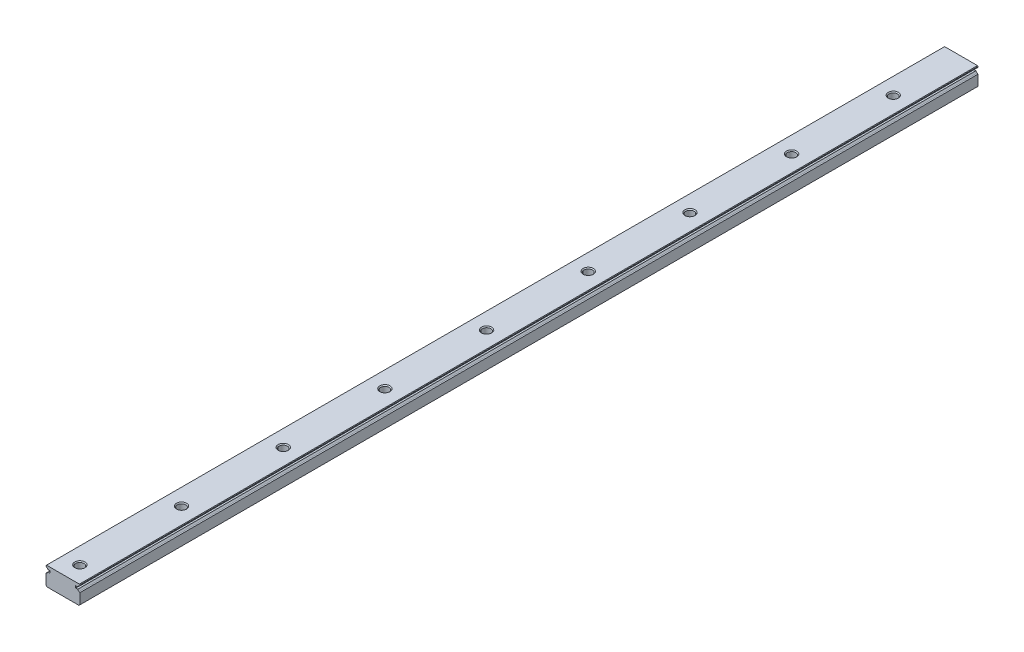
SolidWorks part; units mm, degrees
ref_plane "Plan de face" through (0, 0, 0) normal (0, 0, 1) x (1, 0, 0)
ref_plane "Plan de dessus" through (0, 0, 0) normal (0, 1, 0) x (1, 0, 0)
ref_plane "Plan de droite" through (0, 0, 0) normal (1, 0, 0) x (0, 0, -1)
ref_plane "Plan1" through (0, 0, 0) normal (0, -1, 0) x (1, 0, 0)
sketch "Esquisse1" plane through (0, 0, 0) normal (0, -1, 0) x (1, 0, 0)
  line L0 (-10, -280) -> (10, -280)
  line L1 (10, -280) -> (10, 250)
  line L2 (10, 250) -> (-10, 250)
  line L3 (-10, 250) -> (-10, -280)
  dimension "D1" = 530
  dimension "D2" = 20
extrude "Boss.-Extru.1" add sketch "Esquisse1" against normal blind 11
sketch "Esquisse2" plane through (0, 0, -280) normal (0, 0, -1) x (-1, 0, 0)
  line L0 (10, 7.9) -> (10, 10.2238)
  line L1 (10, 10.2238) -> (9.44, 9.9006)
  line L2 (8.7177, 9.1) -> (7.5, 9.1)
  line L3 (7.5, 9.1) -> (7.5, 7.9)
  line L4 (7.5, 7.9) -> (10, 7.9)
  arc A0 (9.44, 9.9006) -> (8.7177, 9.1) centre (10.315, 8.385) ccw
extrude "Enlèv. mat.-Extru.1" cut sketch "Esquisse2" against normal through all
sketch "Esquisse3" plane through (0, 0, -280) normal (0, 0, -1) x (-1, 0, 0)
  line L0 (9.44, 7.0994) -> (10, 6.7761)
  line L1 (10, 6.7761) -> (10, 7.9)
  line L2 (10, 7.9) -> (8.7177, 7.9)
  arc A0 (8.7177, 7.9) -> (9.44, 7.0994) centre (10.315, 8.615) ccw
extrude "Enlèv. mat.-Extru.2" cut sketch "Esquisse3" against normal through all
sketch "Esquisse4" plane through (0, 0, -280) normal (0, 0, -1) x (-1, 0, 0)
  line L0 (-10, 9.1) -> (-10, 6.7761)
  line L1 (-10, 6.7761) -> (-9.44, 7.0994)
  line L2 (-8.7177, 7.9) -> (-7.5, 7.9)
  line L3 (-7.5, 7.9) -> (-7.5, 9.1)
  line L4 (-7.5, 9.1) -> (-10, 9.1)
  arc A0 (-9.44, 7.0994) -> (-8.7177, 7.9) centre (-10.315, 8.615) ccw
extrude "Enlèv. mat.-Extru.3" cut sketch "Esquisse4" against normal through all
sketch "Esquisse5" plane through (0, 0, -280) normal (0, 0, -1) x (-1, 0, 0)
  line L0 (-9.44, 9.9006) -> (-10, 10.2239)
  line L1 (-10, 10.2239) -> (-10, 9.1)
  line L2 (-10, 9.1) -> (-8.7177, 9.1)
  arc A0 (-8.7177, 9.1) -> (-9.44, 9.9006) centre (-10.315, 8.385) ccw
extrude "Enlèv. mat.-Extru.4" cut sketch "Esquisse5" against normal through all
hole_wizard "Perçage1" positions "Esquisse7" profile "Esquisse6" legacy
sketch "Esquisse7" plane through (0, 11, 0) normal (0, 1, 0) x (1, 0, 0)
  point P0 (0, -180)
  point P1 (0, -120)
  point P2 (0, 60)
  point P3 (0, 180)
sketch "Esquisse6" plane through (0, 11, 180) normal (1, 0, 0) x (0, 0, 1)
  line L0 (0, 0) -> (0, 11)
  line L1 (0, 11) -> (2.4585, 11)
  line L2 (2.4585, 11) -> (2.4585, 0)
  line L3 (2.4585, 0) -> (0, 0)
  line L4 (0, 110) -> (0, -10) construction
  dimension "Diamètre" = 4.917
  dimension "Profondeur" = 11
hole_wizard "Perçage2" positions "Esquisse9" profile "Esquisse8" legacy end condition through all
sketch "Esquisse9" plane through (0, 0, 0) normal (0, -1, 0) x (-1, 0, 0)
  point P0 (0, -240)
  point P1 (0, -60)
  point P2 (0, 0)
  point P3 (0, 120)
  point P4 (0, 240)
sketch "Esquisse8" plane through (0, 0, 240) normal (1, 0, 0) x (0, 0, -1)
  line L0 (0, 0) -> (0, 11)
  line L1 (0, 11) -> (2.4585, 11)
  line L2 (2.4585, 11) -> (2.4585, 0)
  line L3 (2.4585, 0) -> (0, 0)
  line L4 (0, 110) -> (0, -10) construction
  dimension "Diamètre" = 4.917
  dimension "Profondeur" = 11
chamfer "Chanfrein1" distance 0.5415 angle 45 20 edges at (0, 11, -242.4585) (0, 11, -2.4585) (0, 0, -2.4585) (0, 0, -57.5415) (0, 11, -122.4585) (0, 0, -122.4585) (0, 0, -177.5415) (0, 11, 57.5415) (0, 0, -242.4585) (0, 11, -57.5415) (-10, 0, -15) (0, 11, -177.5415) (10, 0, -15) (0, 0, 182.4585) (0, 0, 57.5415) (0, 0, 122.4585) (0, 11, 122.4585) (0, 11, 237.5415) (0, 0, 237.5415) (0, 11, 182.4585)
chamfer "Chanfrein2" distance 0.3 angle 45 2 edges at (-10, 11, -15) (10, 11, -15)
pattern_linear "Répétition linéaire1" [suppressed] count 9 spacing 60
